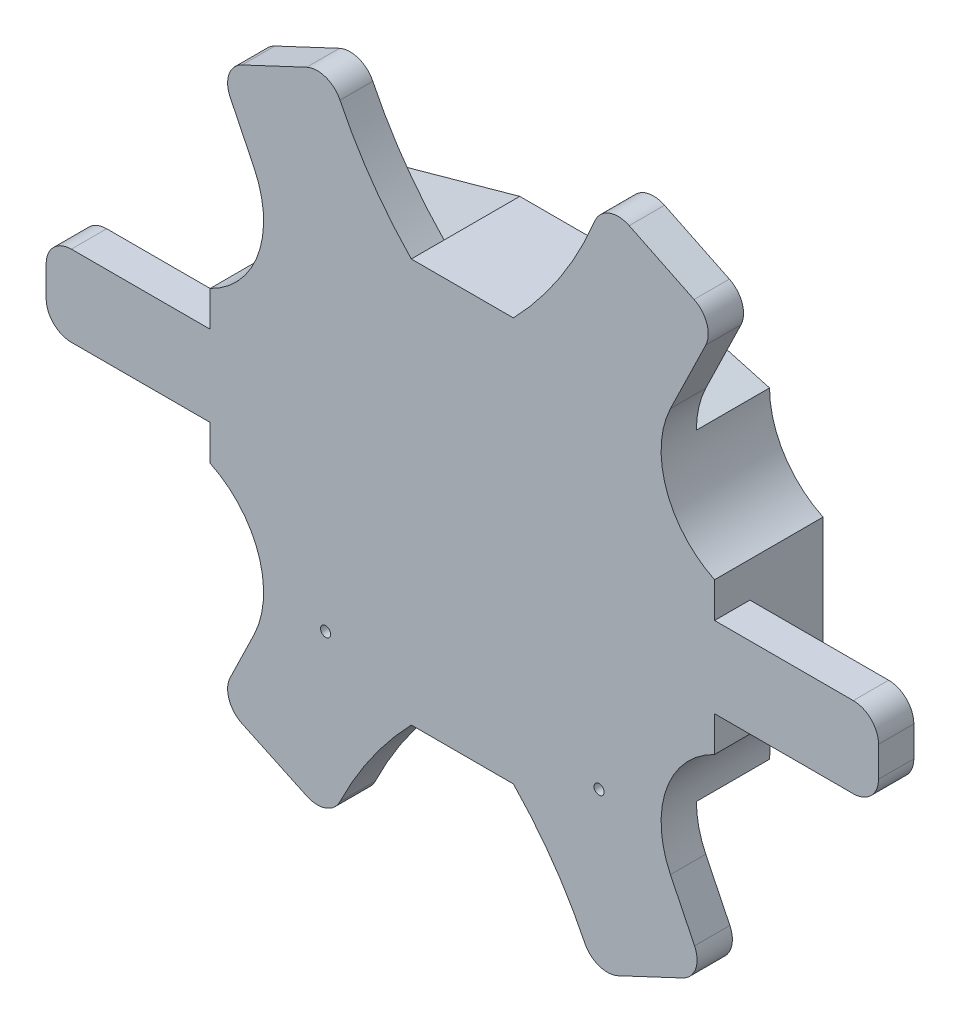
SolidWorks part; units mm, degrees
ref_plane "前视基准面" through (0, 0, 0) normal (0, 0, 1) x (1, 0, 0)
ref_plane "上视基准面" through (0, 0, 0) normal (0, 1, 0) x (1, 0, 0)
ref_plane "右视基准面" through (0, 0, 0) normal (1, 0, 0) x (0, 0, -1)
sketch "草图1" plane through (0, 0, 0) normal (0, 0, 1) x (1, 0, 0)
  line L0 (-50, -40) -> (-32.5, -40)
  line L1 (-50, 40) -> (50, 40)
  line L2 (-50, 40) -> (-50, -40)
  line L3 (-50, -40) -> (50, -40)
  line L4 (50, 40) -> (50, -40)
  line L5 (-50, 40) -> (50, -40) construction
  line L6 (-50, -40) -> (50, 40) construction
  line L7 (-32.5, -40) -> (32.5, -40)
  line L8 (-32.5, -40) -> (-32.5, 40)
  line L9 (-32.5, 40) -> (32.5, 40)
  line L10 (32.5, -40) -> (32.5, 40)
  line L11 (-32.5, -40) -> (32.5, 40) construction
  line L12 (-32.5, 40) -> (32.5, -40) construction
  line L13 (-50, 15) -> (50, 15)
  line L14 (-50, 15) -> (-50, -15)
  line L15 (-50, -15) -> (50, -15)
  line L16 (50, 15) -> (50, -15)
  line L17 (-50, 15) -> (50, -15) construction
  line L18 (-50, -15) -> (50, 15) construction
  line L19 (0, 0) -> (0, -24.7451) construction
  line L20 (0, -24.7451) -> (0, 0) construction
  line L21 (0, 0) -> (19.4056, 0) construction
  arc A0 (-50, -15) -> (-41.25, -40) centre (-58.125, -31.875) cw
  arc A1 (50, -15) -> (41.25, -40) centre (58.125, -31.875) ccw
  arc A2 (50, 15) -> (41.25, 40) centre (58.125, 31.875) cw
  arc A3 (-50, 15) -> (-41.25, 40) centre (-58.125, 31.875) ccw
  point P0 (0, 0)
  point P6 (0, 0)
  point P11 (0, 0)
  dimension "D1" = 100
  dimension "D2" = 80
  dimension "D3" = 65
  dimension "D4" = 30
  dimension "D5" = 0
extrude "凸台-拉伸1" add sketch "草图1" along normal blind 21.5 contours L8 L13 L10 L1 | A3 L13 L8 L1 | L13 A2 L1 L10 | L10 L15 L4 L13 | L8 L15 L10 L13 | L2 L15 L8 L13 | L15 A0 L3 L8 | L15 L8 L3 L10 | A1 L15 L10 L3
sketch "草图2" plane through (0, 0, 21.5) normal (0, 0, 1) x (1, 0, 0)
  line L0 (-41.25, 40) -> (41.25, 40) construction
  line L5 (41.25, 40) -> (0, 40) construction
  line L6 (-41.25, 40) -> (-56.5468, 71.4803)
  line L11 (0, 0) -> (0, 40) construction
  line L12 (10.1194, 40) -> (41.25, 40)
  line L13 (-87.5, 15) -> (-12.5, 15)
  line L14 (-41.25, 40) -> (-56.5468, 71.4803)
  line L16 (-56.5468, 71.4803) -> (-31.3626, 83.7177)
  line L19 (-87.5, 15) -> (-87.5, -15)
  line L20 (-10.1194, 40) -> (-41.25, 40)
  line L21 (56.5468, 71.4803) -> (31.3626, 83.7177)
  line L22 (41.25, 40) -> (56.5468, 71.4803)
  line L23 (-50, 15) -> (-50, -15) construction
  line L24 (-50, -15) -> (-50, 0) construction
  line L25 (-50, 0) -> (50, 0) construction
  line L26 (50, 15) -> (50, -15) construction
  line L27 (-10.1194, -40) -> (-41.25, -40)
  line L28 (-41.25, -40) -> (-56.5468, -71.4803)
  line L29 (-56.5468, -71.4803) -> (-31.3626, -83.7177)
  line L30 (56.5468, -71.4803) -> (31.3626, -83.7177)
  line L31 (41.25, -40) -> (56.5468, -71.4803)
  line L32 (10.1194, -40) -> (41.25, -40)
  line L33 (-87.5, -15) -> (-12.5, -15)
  line L34 (-12.5, 15) -> (-12.5, -15)
  line L35 (-87.5, 15) -> (-12.5, -15) construction
  line L36 (-87.5, -15) -> (-12.5, 15) construction
  line L37 (87.5, -15) -> (12.5, -15)
  line L38 (12.5, 15) -> (12.5, -15)
  line L39 (87.5, 15) -> (12.5, 15)
  line L40 (87.5, 15) -> (87.5, -15)
  arc A0 (-31.3626, 83.7177) -> (-10.1194, 40) centre (45.9871, 94.2833) ccw
  arc A1 (31.3626, 83.7177) -> (10.1194, 40) centre (-45.9871, 94.2833) cw
  arc A2 (-31.3626, -83.7177) -> (-10.1194, -40) centre (45.9871, -94.2833) cw
  arc A3 (31.3626, -83.7177) -> (10.1194, -40) centre (-45.9871, -94.2833) ccw
  line M6 (41.25, 40) -> (-41.25, 40)
  line M8 (-50, 15) -> (-50, -15)
  line M10 (-41.25, -40) -> (41.25, -40)
  line M12 (50, -15) -> (50, 15)
  dimension "D1" = 35
  dimension "D2" = 28
  dimension "D3" = 75
extrude "凸台-拉伸2" add sketch "草图2" against normal blind 7 contours L40 L39 L37 M12 | L21 A1 L22 M6 | A0 L16 L6 M6 | L19 L33 L13 M8 | L29 A2 L28 M10 | A3 L30 L31 M10
sketch "草图6" plane through (0, 0, 0) normal (0, 0, -1) x (-1, 0, 0)
  line L0 (10.1194, 40) -> (39.3958, 31.875)
  line L1 (39.3958, 31.875) -> (56.8372, 38.3489)
  line L2 (56.8372, 38.3489) -> (0, 62.6398)
  line L3 (0, 62.6398) -> (10.1194, 40)
  line L4 (-10.1194, 40) -> (-39.3958, 31.875)
  line L5 (41.25, 40) -> (-41.25, 40) construction
  line L6 (-41.25, 40) -> (-10.1194, 40) construction
  line L7 (-39.3958, 31.875) -> (-63.924, 42.3578)
  line L8 (-63.924, 42.3578) -> (-39.3958, 57.1479)
  line L9 (-39.3958, 57.1479) -> (-10.1194, 40)
  line L10 (-41.25, -40) -> (-10.1194, -40)
  line L11 (-10.1194, -40) -> (-39.3958, -31.875)
  line L12 (-39.3958, -31.875) -> (-55.112, -31.875)
  line L13 (-55.112, -31.875) -> (-41.25, -40)
  line L14 (41.25, -40) -> (10.1194, -40)
  line L15 (10.1194, -40) -> (39.3958, -31.875)
  line L16 (39.3958, -31.875) -> (58.125, -33.6788)
  line L17 (58.125, -33.6788) -> (41.25, -40)
  arc A0 (41.25, 40) -> (50, 15) centre (58.125, 31.875) ccw construction
  arc A1 (-50, 15) -> (-41.25, 40) centre (-58.125, 31.875) ccw construction
  arc A2 (-41.25, -40) -> (-50, -15) centre (-58.125, -31.875) ccw construction
  arc A3 (50, -15) -> (41.25, -40) centre (58.125, -31.875) ccw construction
extrude "切除-拉伸21" cut sketch "草图6" against normal blind 15 contours L3 L0 L1 L2
sketch "草图7" plane through (0, 0, 0) normal (0, 0, -1) x (-1, 0, 0)
  line L0 (-10.1194, -40) -> (-39.3958, -31.875)
  line L1 (-39.3958, -31.875) -> (-53.3584, -39.7712)
  line L2 (-53.3584, -39.7712) -> (-19.0866, -55.9873)
  line L3 (-19.0866, -55.9873) -> (-10.1194, -40)
  arc A0 (-41.25, -40) -> (-50, -15) centre (-58.125, -31.875) ccw construction
extrude "切除-拉伸23" cut sketch "草图7" against normal blind 14.5
sketch "草图9" plane through (0, 0, 0) normal (0, 0, -1) x (-1, 0, 0)
  line L0 (-10.1194, 40) -> (-39.3958, 31.875)
  line L1 (-39.3958, 31.875) -> (-58.125, 43.8836)
  line L2 (-58.125, 43.8836) -> (-7.923, 48.831)
  line L3 (-7.923, 48.831) -> (-10.1194, 40)
  arc A0 (-50, 15) -> (-41.25, 40) centre (-58.125, 31.875) ccw construction
  arc A1 (-50, 15) -> (-41.25, 40) centre (-58.125, 31.875) ccw construction
extrude "切除-拉伸24" cut sketch "草图9" against normal blind 14.5
sketch "草图10" plane through (0, 0, 0) normal (0, 0, -1) x (-1, 0, 0)
  line L0 (10.1194, 40) -> (42.2669, 21.9099)
  line L1 (42.2669, 21.9099) -> (59.8046, 30.9549)
  line L2 (59.8046, 30.9549) -> (0, 68.2027)
  line L3 (0, 68.2027) -> (10.1194, 40)
  arc A0 (39.3958, 31.875) -> (50, 15) centre (58.125, 31.875) ccw construction
extrude "切除-拉伸25" cut sketch "草图10" against normal blind 14.5
sketch "草图11" plane through (0, 0, 0) normal (0, 0, -1) x (-1, 0, 0)
  line L0 (10.1194, -40) -> (39.3958, -31.875)
  line L1 (39.3958, -31.875) -> (61.5861, -40)
  line L2 (61.5861, -40) -> (5.3442, -59.2957)
  line L3 (5.3442, -59.2957) -> (10.1194, -40)
  arc A0 (50, -15) -> (41.25, -40) centre (58.125, -31.875) ccw construction
extrude "切除-拉伸27" cut sketch "草图11" against normal blind 14.5 contours L3 L0 L1 L2
sketch "草图12" plane through (0, 0, 14.5) normal (0, 0, -1) x (-1, 0, 0)
  line L0 (10.1194, 40) -> (42.2669, 21.9099)
  line L1 (42.2669, 21.9099) -> (51.0834, 30.9549)
  line L2 (51.0834, 30.9549) -> (39.3958, 31.875)
  line L3 (39.3958, 31.875) -> (10.1194, 40) construction
  line L4 (39.3958, 31.875) -> (10.1194, 40)
  arc A0 (39.3958, 31.875) -> (42.2669, 21.9099) centre (58.125, 31.875) ccw construction
extrude "切除-拉伸28" cut sketch "草图12" against normal blind 0.5
sketch "草图13" plane through (0, 0, 14.5) normal (0, 0, -1) x (-1, 0, 0)
  line L0 (56.5468, -71.4803) -> (52.1763, -62.4859)
  line L1 (41.25, -40) -> (56.5468, -71.4803) construction
  line L3 (6.5457, -78.4133) -> (26.2576, -99.2847)
  line L4 (26.2576, -99.2847) -> (85.3933, -94.9365)
  line L5 (85.3933, -94.9365) -> (79.8856, -70.4496)
  line L6 (79.8856, -70.4496) -> (52.1763, -62.4859)
  line L7 (-56.5468, -71.4803) -> (-52.1763, -62.4859)
  line L8 (-41.25, -40) -> (-56.5468, -71.4803) construction
  line L10 (-3.3103, -66.9831) -> (-32.1225, -112.3189)
  line L11 (-32.1225, -112.3189) -> (-60.0284, -104.2987)
  line L12 (-60.0284, -104.2987) -> (-105.3484, -70.4496)
  line L13 (-105.3484, -70.4496) -> (-52.1763, -62.4859)
  line L14 (-52.1763, -62.4859) -> (-12.6565, -81.6893)
  line L15 (0, 0) -> (-120.4222, 0)
  line L16 (-120.4222, 0) -> (133.5136, 0)
  line L17 (-32.1225, 112.3189) -> (-60.0284, 104.2987)
  line L18 (-52.1763, 62.4859) -> (-12.6565, 81.6893)
  line L19 (-105.3484, 70.4496) -> (-52.1763, 62.4859)
  line L20 (-60.0284, 104.2987) -> (-105.3484, 70.4496)
  line L21 (79.8856, 70.4496) -> (52.1763, 62.4859)
  line L22 (85.3933, 94.9365) -> (79.8856, 70.4496)
  line L23 (26.2576, 99.2847) -> (85.3933, 94.9365)
  line L24 (6.5457, 78.4133) -> (26.2576, 99.2847)
  line L25 (52.1763, 62.4859) -> (6.5457, 78.4133)
  line L26 (-14.6432, 80.7239) -> (-32.1225, 112.3189)
  line L27 (52.1763, -62.4859) -> (56.5468, -71.4803)
  line L28 (52.1763, -62.4859) -> (8.4478, -83.7344)
  line L29 (56.5468, -71.4803) -> (12.8183, -92.7288)
  line L30 (8.4478, -83.7344) -> (12.8183, -92.7288)
  line L31 (-56.5468, -71.4803) -> (-52.1763, -62.4859)
  line L32 (-56.5468, -71.4803) -> (0.3344, -99.1199)
  line L33 (-52.1763, -62.4859) -> (4.705, -90.1256)
  line L34 (0.3344, -99.1199) -> (4.705, -90.1256)
  line L35 (52.1763, 62.4859) -> (56.5468, 71.4803)
  line L36 (52.1763, 62.4859) -> (-9.5134, 92.4621)
  line L37 (56.5468, 71.4803) -> (-5.1428, 101.4564)
  line L38 (-9.5134, 92.4621) -> (-5.1428, 101.4564)
  line L39 (-52.1763, 62.4859) -> (-56.5468, 71.4803)
  line L40 (-52.1763, 62.4859) -> (-11.0572, 82.4664)
  line L41 (-56.5468, 71.4803) -> (-15.4278, 91.4608)
  line L42 (-11.0572, 82.4664) -> (-15.4278, 91.4608)
  arc M12 (10.1194, -40) -> (31.3626, -83.7177) centre (-45.9871, -94.2833) cw
  line M13 (31.3626, -83.7177) -> (56.5468, -71.4803)
  line M14 (56.5468, -71.4803) -> (41.25, -40)
  dimension "D1" = 10
extrude "切除-拉伸32" cut sketch "草图13" against normal blind 10 contours L35 L37 L24 L36 | L41 L39 L18 L26 | L7 L32 L10 L14 | L28 M14 M12 M13
sketch "草图14" plane through (0, 0, 14.5) normal (0, 0, -1) x (-1, 0, 0)
  line L0 (50, 15) -> (50, -15) construction
  line L1 (87.5, -15) -> (50, -15)
  line L2 (87.5, -15) -> (87.5, -8)
  line L3 (87.5, -8) -> (50, -8)
  line L4 (50, -15) -> (50, -8)
  line L6 (87.5, 15) -> (50, 15)
  line L7 (87.5, 15) -> (87.5, 8)
  line L8 (87.5, 8) -> (50, 8)
  line L9 (50, 15) -> (50, 8)
  line L10 (0, 0) -> (0, 76.7434)
  line L11 (-87.5, 8) -> (-50, 8)
  line L12 (-50, 15) -> (-50, 8)
  line L13 (-87.5, 15) -> (-50, 15)
  line L14 (-87.5, 15) -> (-87.5, 8)
  line L15 (-87.5, -8) -> (-50, -8)
  line L16 (-50, -15) -> (-50, -8)
  line L17 (-87.5, -15) -> (-50, -15)
  line L18 (-87.5, -15) -> (-87.5, -8)
  line M9 (87.5, -15) -> (87.5, 15)
  line M11 (50, 15) -> (50, -15)
  line M12 (50, -15) -> (87.5, -15)
  dimension "D1" = 7
  dimension "D2" = 7
extrude "切除-拉伸33" cut sketch "草图14" against normal blind 10 contours L3 M9 M11 M12 | L18 L17 L16 L15 | L8 L9 L6 L7 | L11 L12 L13 L14
sketch "草图15" plane through (0, 0, 0) normal (0, 0, -1) x (-1, 0, 0)
  line L0 (39.3958, -31.875) -> (27.8329, -35.084)
  line L1 (0, 0) -> (0, -31.875) construction
  line L2 (10.1194, -40) -> (39.3958, -31.875) construction
  line L3 (27.8329, -35.084) -> (27.0975, -32.4342)
  line L4 (0, -31.875) -> (0, 0) construction
  line L5 (-18.8584, 0) -> (18.8584, 0) construction
  circle A2 centre (27.0975, -32.4342) radius 1
  circle A3 centre (-27.0975, -32.4342) radius 1
  dimension "D2" = 2.75
  dimension "D3" = 2
  dimension "D1" = 12
  dimension "D4" = 2.75
extrude "切除-拉伸34" cut sketch "草图15" against normal blind 30 contours A3 | A2
sketch "草图17" plane through (0, 0, 0) normal (0, 0, -1) x (-1, 0, 0)
  line L0 (-39.3958, 31.875) -> (-10.1194, 40)
  line L1 (-10.1194, 40) -> (10.1194, 40)
  line L2 (10.1194, 40) -> (0, 40)
  line L3 (0, 40) -> (0, 22.0171)
  line L4 (39.3958, 31.875) -> (10.1194, 40)
  line L5 (10.1194, 40) -> (42.2669, 21.9099)
  arc A0 (42.2669, 21.9099) -> (39.3958, 31.875) centre (58.125, 31.875) cw
  line M7 (42.2669, 21.9099) -> (10.1194, 40)
extrude "凸台-拉伸3" add sketch "草图17" against normal blind 20 contours A0 L4 M7
sketch "草图18" plane through (0, 0, 0) normal (0, 0, -1) x (-1, 0, 0)
  line L0 (0, 0) -> (14.8691, 0)
  circle A0 centre (-27.0975, -32.4342) radius 1
  circle A1 centre (27.0975, -32.4342) radius 1
  circle A2 centre (27.0975, 32.4342) radius 1
  circle A3 centre (-27.0975, 32.4342) radius 1
extrude "切除-拉伸35" cut sketch "草图18" against normal blind 20 contours A3 | A2
sketch "草图19" plane through (0, 0, 0) normal (0, 0, -1) x (-1, 0, 0)
  line L0 (-50, 15) -> (-50, -15)
  line L1 (-50, -15) -> (-50, 0)
  line L2 (-50, 0) -> (-47.25, 0)
  line L3 (50, 15) -> (50, -15)
  line L4 (50, -15) -> (50, 0)
  line L5 (50, 0) -> (47.25, 0)
  circle A0 centre (-47.25, 0) radius 1
  circle A1 centre (47.25, 0) radius 1
  dimension "D2" = 2
  dimension "D4" = 2
  dimension "D1" = 2.75
  dimension "D3" = 2.75
extrude "切除-拉伸36" cut sketch "草图19" against normal blind 20
sketch "草图20" plane through (0, 0, 0) normal (0, 0, -1) x (-1, 0, 0)
  line L1 (-27.5, 17.5) -> (27.5, 17.5)
  line L2 (-27.5, 17.5) -> (-27.5, -17.5)
  line L3 (-27.5, -17.5) -> (27.5, -17.5)
  line L4 (27.5, 17.5) -> (27.5, -17.5)
  line L5 (-27.5, 17.5) -> (27.5, -17.5) construction
  line L6 (-27.5, -17.5) -> (27.5, 17.5) construction
  point P0 (0, 0)
  dimension "D1" = 35
  dimension "D2" = 55
extrude "切除-拉伸37" cut sketch "草图20" against normal blind 20
sketch "草图21" plane through (-22.6362, 52.9656, 0) normal (0.393, -0.9195, 0) x (0.9195, 0.393, 0)
  line L1 (-22.4348, 15) -> (12.766, 15)
  line L2 (-22.4348, 15) -> (-22.4348, 4.0261)
  line L3 (-22.4348, 4.0261) -> (12.766, 4.0261)
  line L4 (12.766, 15) -> (12.766, 4.0261)
extrude "切除-拉伸38" cut sketch "草图21" against normal blind 26
ref_plane "基准面1" through (-51.2874, 62.9178, 14.5) normal (0.393, -0.9195, 0) x (-0.9195, -0.393, 0)
sketch "草图25" plane through (-34.5297, 71.0607, 0) normal (-0.4371, 0.8994, 0) x (0.8994, 0.4371, 0)
  line L1 (-18.6313, -15) -> (-22.9652, -15)
  line L2 (-18.6313, -15) -> (-18.6313, -11.4117)
  line L3 (-18.6313, -11.4117) -> (-22.9652, -11.4117)
  line L4 (-22.9652, -15) -> (-22.9652, -11.4117)
extrude "切除-拉伸41" cut sketch "草图25" against normal blind 26
sketch "草图26" plane through (17.6466, -8.5748, 0) normal (0.8994, -0.4371, 0) x (0, 0, -1)
  line L0 (-21.5, 79.0059) -> (-14.5, 79.0059)
sketch "草图28" plane through (0, 0, 14.5) normal (0, 0, -1) x (-1, 0, 0)
  line L0 (-52.1763, 62.4859) -> (-50.4281, 58.8882)
  line L1 (-52.1763, 62.4859) -> (-16.9488, 79.6036)
  line L2 (-50.4281, 58.8882) -> (-15.2006, 76.0058)
  line L3 (-16.9488, 79.6036) -> (-15.2006, 76.0058)
  line L4 (-41.25, 40) -> (-52.1763, 62.4859) construction
  line L5 (0, 0) -> (0, 49.7835)
  line L6 (0, 49.7835) -> (0, 0)
  line L7 (0, -1.8015) -> (-48.6857, -1.8015)
  line L8 (-48.6857, -1.8015) -> (48.6857, -1.8015)
  line L9 (50.4281, 58.8882) -> (15.2006, 76.0058)
  line L10 (16.9488, 79.6036) -> (15.2006, 76.0058)
  line L11 (52.1763, 62.4859) -> (16.9488, 79.6036)
  line L12 (52.1763, 62.4859) -> (50.4281, 58.8882)
  line L13 (52.1763, -66.089) -> (50.4281, -62.4912)
  line L14 (52.1763, -66.089) -> (16.9488, -83.2067)
  line L15 (16.9488, -83.2067) -> (15.2006, -79.6089)
  line L16 (50.4281, -62.4912) -> (15.2006, -79.6089)
  line L17 (-50.4281, -62.4912) -> (-15.2006, -79.6089)
  line L18 (-16.9488, -83.2067) -> (-15.2006, -79.6089)
  line L19 (-52.1763, -66.089) -> (-16.9488, -83.2067)
  line L20 (-52.1763, -66.089) -> (-50.4281, -62.4912)
  line L21 (-50.4281, -62.4912) -> (-52.1763, -66.089)
  line L22 (-50.4281, -62.4912) -> (-58.7905, -58.4278)
  line L23 (-52.1763, -66.089) -> (-60.5387, -62.0255)
  line L24 (-58.7905, -58.4278) -> (-60.5387, -62.0255)
  line L25 (50.4281, -62.4912) -> (52.1763, -66.089)
  line L26 (50.4281, -62.4912) -> (56.3121, -59.6321)
  line L27 (52.1763, -66.089) -> (58.0603, -63.2298)
  line L28 (56.3121, -59.6321) -> (58.0603, -63.2298)
  dimension "D1" = 4
extrude "切除-拉伸42" cut sketch "草图28" against normal blind 23 contours L13 L16 L15 L14 | L28 L26 L13 L27 | L20 L19 L18 L17 | L22 L24 L23 L20 | L3 L1 L0 L2 | L12 L11 L10 L9
sketch "草图29" plane through (0, 0, 14.5) normal (0, 0, -1) x (-1, 0, 0)
  line L0 (-87.5, 8) -> (-87.5, -8)
  line L1 (-87.5, 8) -> (-82.5, 8)
  line L2 (-87.5, -8) -> (-82.5, -8)
  line L3 (-82.5, 8) -> (-82.5, -8)
  line L4 (87.5, 8) -> (87.5, -8)
  line L5 (87.5, 8) -> (82.5, 8)
  line L6 (87.5, -8) -> (82.5, -8)
  line L7 (82.5, 8) -> (82.5, -8)
  dimension "D1" = 5
  dimension "D2" = 5
extrude "切除-拉伸43" cut sketch "草图29" against normal blind 23
sketch "草图30" plane through (0, 0, 0) normal (0, 0, -1) x (-1, 0, 0)
  line L0 (-27.5, 0) -> (-37.5, 0) construction
  line L1 (-27.5, 17.5) -> (-27.5, -17.5) construction
  line L2 (27.5, 0) -> (37.5, 0) construction
  line L3 (27.5, -17.5) -> (27.5, 17.5) construction
  circle A0 centre (-37.5, 0) radius 1.55
  circle A1 centre (37.5, 0) radius 1.55
  dimension "D2" = 3.1
  dimension "D4" = 3.1
  dimension "D1" = 10
  dimension "D3" = 10
extrude "切除-拉伸44" cut sketch "草图30" against normal blind 10 contours A0 | A1
sketch "草图31" plane through (0, 0, 0) normal (0, 0, -1) x (-1, 0, 0)
  line L0 (37.5, 0) -> (-35.5, 0)
  circle A0 centre (-35.5, 0) radius 1.55
  dimension "D2" = 3.1
  dimension "D1" = 73
extrude "切除-拉伸45" cut sketch "草图31" against normal blind 6.1008
sketch "草图32" plane through (0, 0, 0) normal (0, 0, -1) x (-1, 0, 0)
  circle A0 centre (-37.5, 0) radius 1.55
extrude "凸台-拉伸4" add sketch "草图32" against normal blind 15
sketch "草图33" plane through (0, 0, 0) normal (0, 0, -1) x (-1, 0, 0)
  circle A0 centre (-35.5, 0) radius 1.55
extrude "切除-拉伸46" cut sketch "草图33" against normal blind 12
sketch "草图34" plane through (0, 0, 14.5) normal (0, 0, -1) x (-1, 0, 0)
  line L0 (-50, -8) -> (-77.5, -8)
  line L1 (-82.5, -3) -> (-82.5, 3)
  line L2 (-77.5, 8) -> (-50, 8)
  line L3 (-50, 15) -> (-50, -15) construction
  line L4 (-82.5, 8) -> (-50, 8) construction
  line L5 (-77.5, 8) -> (-82.5, 8)
  line L6 (-82.5, 8) -> (-82.5, 3)
  line L7 (-82.5, -8) -> (-77.5, -8)
  line L8 (-82.5, -3) -> (-82.5, -8)
  arc A0 (-82.5, -3) -> (-77.5, -8) centre (-77.5, -3) ccw
  arc A1 (-77.5, 8) -> (-82.5, 3) centre (-77.5, 3) ccw
  point P13 (-82.5, -8)
  point P16 (-82.5, 8)
  line M6 (-50, 8) -> (-82.5, 8)
  line M7 (-82.5, 8) -> (-82.5, -8)
  line M8 (-82.5, -8) -> (-50, -8)
  dimension "D1" = 5
extrude "切除-拉伸49" cut sketch "草图34" against normal blind 10 contours A0 M7 M8 | A1 M6 M7
sketch "草图35" plane through (0, 0, 14.5) normal (0, 0, -1) x (-1, 0, 0)
  line L0 (50.0163, 8) -> (77.5, 8)
  line L1 (82.5, 8) -> (50, 8) construction
  line L2 (82.5, 8) -> (82.5, -8) construction
  line L3 (82.5, 3) -> (82.5, -3)
  line L4 (77.5, -8) -> (50, -8)
  line L5 (82.5, -8) -> (50, -8) construction
  line L6 (77.5, 8) -> (82.5, 8)
  line L7 (82.5, 8) -> (82.5, -8.4667)
  line L8 (82.5, -8.4667) -> (77.5, -8)
  arc A0 (82.5, 3) -> (77.5, 8) centre (77.5, 3) ccw
  arc A1 (82.5, -3) -> (77.5, -8) centre (77.5, -3) cw
  point P12 (82.5, 8)
  point P15 (82.5, -8)
  line M1 (50, -8) -> (82.5, -8)
  line M2 (82.5, -8) -> (82.5, 8)
  line M3 (82.5, 8) -> (50, 8)
  dimension "D1" = 5
extrude "切除-拉伸50" cut sketch "草图35" against normal blind 25 contours A0 M2 M3 | A1 M2 M1
sketch "草图36" plane through (0, 0, 14.5) normal (0, 0, -1) x (-1, 0, 0)
  line L0 (-45.9309, 61.0734) -> (-33.0777, 67.319)
  line L1 (-48.2428, 54.391) -> (-41.25, 40)
  line L2 (-27.5, 0) -> (27.5, 0)
  line L3 (-27.5, 17.5) -> (-27.5, -17.5) construction
  line L4 (27.5, -17.5) -> (27.5, 17.5) construction
  line L5 (27.5, 0) -> (0, 0)
  line L6 (0, 0) -> (0, 40)
  line L7 (10.1194, 40) -> (-10.1194, 40) construction
  line L8 (-45.9309, -61.0734) -> (-33.0777, -67.319)
  line L9 (33.0777, -67.319) -> (45.9309, -61.0734)
  line L10 (26.265, -64.7156) -> (16.255, -74.7256)
  line L11 (16.255, -74.7256) -> (33.0777, -82.9)
  line L12 (33.0777, -82.9) -> (53.4138, -73.0184)
  line L13 (53.4138, -73.0184) -> (58.1214, -59.4115)
  line L14 (58.1214, -59.4115) -> (48.2428, -54.391)
  line L15 (-26.265, -64.7156) -> (-14.7187, -84.3905)
  line L16 (-14.7187, -84.3905) -> (-54.0273, -84.3905)
  line L17 (-54.0273, -84.3905) -> (-58.9039, -66.2149)
  line L18 (-58.9039, -66.2149) -> (-58.9039, -48.4808)
  line L19 (-58.9039, -48.4808) -> (-48.2428, -54.391)
  line L20 (-26.265, 64.7156) -> (-25.3062, 81.0959)
  line L21 (-25.3062, 81.0959) -> (-42.8998, 80.2776)
  line L22 (-42.8998, 80.2776) -> (-39.5043, 72.9057)
  line L23 (-39.5043, 72.9057) -> (-33.0777, 67.319)
  line L24 (-45.9309, 61.0734) -> (-63.9834, 67.319)
  line L25 (-63.9834, 67.319) -> (-64.7048, 65.234)
  line L26 (-64.7048, 65.234) -> (-70.7158, 54.391)
  line L27 (-70.7158, 54.391) -> (-54.9572, 54.391)
  line L28 (-54.9572, 54.391) -> (-48.2428, 54.391)
  line L29 (26.265, 64.7156) -> (17.7678, 67.6553)
  line L30 (17.7678, 67.6553) -> (26.8486, 84.0357)
  line L31 (26.8486, 84.0357) -> (28.8201, 82.9428)
  line L32 (28.8201, 82.9428) -> (36.6358, 76.1485)
  line L33 (36.6358, 76.1485) -> (33.0777, 67.319)
  line L34 (45.9309, 61.0734) -> (49.061, 72.9057)
  line L35 (49.061, 72.9057) -> (54.9946, 67.7476)
  line L36 (54.9946, 67.7476) -> (55.5142, 56.5762)
  line L37 (55.5142, 56.5762) -> (53.6802, 49.6434)
  line L38 (53.6802, 49.6434) -> (48.2428, 54.391)
  arc A0 (-26.265, 64.7156) -> (-10.1194, 40) centre (45.9871, 94.2833) ccw
  arc A1 (-33.0777, 67.319) -> (-26.265, 64.7156) centre (-30.8925, 62.8218) cw
  arc A2 (-48.2428, 54.391) -> (-45.9309, 61.0734) centre (-43.7457, 56.5762) cw
  arc A3 (48.2428, 54.391) -> (45.9309, 61.0734) centre (43.7457, 56.5762) ccw
  arc A4 (33.0777, 67.319) -> (26.265, 64.7156) centre (30.8925, 62.8218) ccw
  arc A5 (-48.2428, -54.391) -> (-45.9309, -61.0734) centre (-43.7457, -56.5762) ccw
  arc A6 (-33.0777, -67.319) -> (-26.265, -64.7156) centre (-30.8925, -62.8218) ccw
  arc A7 (33.0777, -67.319) -> (26.265, -64.7156) centre (30.8925, -62.8218) cw
  arc A8 (48.2428, -54.391) -> (45.9309, -61.0734) centre (43.7457, -56.5762) cw
  point P11 (-28.1188, 69.7287)
  point P14 (-50.4281, 58.8882)
  arc M2 (-10.1194, 40) -> (-28.1188, 69.7287) centre (45.9871, 94.2833) cw
  line M3 (-28.1188, 69.7287) -> (-50.4281, 58.8882)
  line M4 (-50.4281, 58.8882) -> (-41.25, 40)
  dimension "D1" = 5
  dimension "D2" = 5
extrude "切除-拉伸51" cut sketch "草图36" against normal blind 25 contours L22 L23 L20 L21 M3 M2 | A4 L33 L32 L31 L30 L29 | A3 L38 L37 L36 L35 L34 | L27 L28 L24 L25 L26 M4 M3 | A6 L8 A5 L19 L18 L17 L16 L15 | L14 A8 L9 A7 L10 L11 L12 L13
sketch "草图37" plane through (0, 0, 14.5) normal (0, 0, -1) x (-1, 0, 0)
  line L0 (-50.4281, 58.8882) -> (-49.4563, 56.8882)
  line L1 (-50.4281, 58.8882) -> (-22.5323, 72.4432)
  line L2 (-49.4563, 56.8882) -> (-21.5605, 70.4432)
  line L3 (-22.5323, 72.4432) -> (-21.5605, 70.4432)
  line L4 (-41.25, 40) -> (-50.4281, 58.8882) construction
  line L5 (0, 0) -> (20.5618, 0)
  line L6 (20.5618, 0) -> (0, 0)
  line L7 (0, 0) -> (0, 31.9309)
  line L8 (49.4563, 56.8882) -> (21.5605, 70.4432)
  line L9 (22.5323, 72.4432) -> (21.5605, 70.4432)
  line L10 (50.4281, 58.8882) -> (22.5323, 72.4432)
  line L11 (50.4281, 58.8882) -> (49.4563, 56.8882)
  line L12 (50.4281, -58.8882) -> (49.4563, -56.8882)
  line L13 (50.4281, -58.8882) -> (22.5323, -72.4432)
  line L14 (22.5323, -72.4432) -> (21.5605, -70.4432)
  line L15 (49.4563, -56.8882) -> (21.5605, -70.4432)
  line L16 (-49.4563, -56.8882) -> (-21.5605, -70.4432)
  line L17 (-22.5323, -72.4432) -> (-21.5605, -70.4432)
  line L18 (-50.4281, -58.8882) -> (-22.5323, -72.4432)
  line L19 (-50.4281, -58.8882) -> (-49.4563, -56.8882)
  arc M11 (-10.1194, 40) -> (-28.1188, 69.7287) centre (45.9871, 94.2833) cw
  dimension "D1" = 2
extrude "切除-拉伸52" cut sketch "草图37" against normal blind 25 contours L19 L18 L17 L16 | L12 L15 L14 L13 | L11 L10 L9 L8 | L3 L1 L2 M11
sketch "草图38" plane through (0, 0, 14.5) normal (0, 0, -1) x (-1, 0, 0)
  line L0 (-41.25, 40) -> (-48.2428, 54.391)
  line L1 (-45.9309, 61.0734) -> (-33.0777, 67.319)
  line L2 (-48.2428, 54.391) -> (-80.4737, 72.3605)
  line L3 (-80.4737, 72.3605) -> (-37.0273, 93.4719)
  line L4 (-37.0273, 93.4719) -> (-21.2855, 73.9284)
  line L5 (-21.2855, 73.9284) -> (-26.265, 64.7156)
  line L6 (0, 0) -> (-21.2855, 0)
  line L7 (-21.2855, 0) -> (0, 0)
  line L8 (0, 0) -> (0, -15.6861)
  arc A0 (-45.9309, 61.0734) -> (-48.2428, 54.391) centre (-43.7457, 56.5762) ccw
  arc A1 (-10.1194, 40) -> (-26.265, 64.7156) centre (45.9871, 94.2833) cw
  arc A2 (-33.0777, 67.319) -> (-26.265, 64.7156) centre (-30.8925, 62.8218) cw
  point P8 (-50.4281, 58.8882)
  point P14 (-28.1188, 69.7287)
  arc M6 (-10.1194, 40) -> (-28.1188, 69.7287) centre (45.9871, 94.2833) cw
  line M7 (-28.1188, 69.7287) -> (-50.4281, 58.8882)
  line M8 (-50.4281, 58.8882) -> (-41.25, 40)
  dimension "D1" = 5
  dimension "D2" = 5
extrude "切除-拉伸55" cut sketch "草图38" against normal blind 25 contours A2 M7 M6 | A0 M7 M8
sketch "草图39" plane through (0, 0, 15) normal (0, 0, -1) x (-1, 0, 0)
  line L0 (48.2428, 54.391) -> (26.265, 64.7156)
  line L1 (26.265, 64.7156) -> (26.265, 71.3681)
  line L2 (26.265, 71.3681) -> (43.7457, 64.7156)
  line L3 (43.7457, 64.7156) -> (54.4532, 55.7897)
  line L4 (54.4532, 55.7897) -> (48.2428, 54.391)
  arc A0 (28.3658, 67.1364) -> (26.265, 64.7156) centre (30.8925, 62.8218) ccw construction
  arc A1 (10.1194, 40) -> (26.265, 64.7156) centre (-45.9871, 94.2833) ccw construction
extrude "切除-拉伸56" cut sketch "草图39" against normal blind 25
sketch "草图40" plane through (0, 0, 15) normal (0, 0, -1) x (-1, 0, 0)
  line L0 (46.0278, 49.8326) -> (41.25, 40)
  line L1 (41.25, 40) -> (48.2428, 54.391)
  line L2 (30.8708, 62.5441) -> (43.655, 56.5442)
  line L3 (24.2481, 60.2007) -> (21.2149, 69.5097)
  line L4 (21.2149, 69.5097) -> (39.6913, 70.9899)
  line L5 (39.6913, 70.9899) -> (58.6843, 58.0178)
  line L6 (58.6843, 58.0178) -> (64.7781, 52.0179)
  line L7 (64.7781, 52.0179) -> (46.0278, 49.8326)
  arc A0 (24.2481, 60.2007) -> (10.1194, 40) centre (-45.9871, 94.2833) cw
  arc A1 (10.1194, 40) -> (26.265, 64.7156) centre (-45.9871, 94.2833) ccw construction
  arc A2 (43.655, 56.5442) -> (46.0278, 49.8326) centre (41.5307, 52.0179) cw
  arc A3 (24.2481, 60.2007) -> (30.8708, 62.5441) centre (28.7465, 58.0178) cw
  point P16 (26.2616, 64.7073)
  line M2 (41.25, 40) -> (48.2428, 54.391)
  line M3 (48.2428, 54.391) -> (26.265, 64.7156)
  arc M4 (26.265, 64.7156) -> (10.1194, 40) centre (-45.9871, 94.2833) cw
  dimension "D1" = 5
  dimension "D2" = 5
extrude "切除-拉伸59" cut sketch "草图40" against normal blind 25 contours A3 L2 A2 M4 M2 M3
sketch "草图41" plane through (0, 0, 14.5) normal (0, 0, -1) x (-1, 0, 0)
  line L0 (-48.2428, -54.391) -> (-26.265, -64.7156)
  line L1 (-26.265, -64.7156) -> (-33.3072, -81.924)
  line L2 (-33.3072, -81.924) -> (-55.0773, -68.9395)
  line L3 (-55.0773, -68.9395) -> (-59.7694, -58.1933)
  line L4 (-59.7694, -58.1933) -> (-48.2428, -54.391)
extrude "切除-拉伸60" cut sketch "草图41" against normal blind 25
sketch "草图42" plane through (0, 0, 14.5) normal (0, 0, -1) x (-1, 0, 0)
  line L0 (-41.25, -40) -> (-46.0287, -49.8343)
  line L1 (-43.6574, -56.5451) -> (-30.8755, -62.5497)
  line L2 (-46.0287, -49.8343) -> (-48.2428, -54.391)
  line L3 (-48.2428, -54.391) -> (-26.265, -64.7156)
  line L4 (-26.265, -64.7156) -> (-24.251, -60.2066)
  arc A0 (-10.1194, -40) -> (-24.251, -60.2066) centre (45.9871, -94.2833) ccw
  arc A1 (-30.8755, -62.5497) -> (-24.251, -60.2066) centre (-28.7495, -58.0241) ccw
  arc A2 (-43.6574, -56.5451) -> (-46.0287, -49.8343) centre (-41.5315, -52.0195) cw
  point P11 (-26.265, -64.7156)
  point P14 (-48.2428, -54.391)
  line M6 (-41.25, -40) -> (-48.2428, -54.391)
  line M7 (-48.2428, -54.391) -> (-26.265, -64.7156)
  arc M8 (-26.265, -64.7156) -> (-10.1194, -40) centre (45.9871, -94.2833) cw
  dimension "D1" = 5
  dimension "D2" = 5
extrude "切除-拉伸61" cut sketch "草图42" against normal blind 25 contours A2 M7 M6 | A1 M7 M8
sketch "草图43" plane through (0, 0, 14.5) normal (0, 0, -1) x (-1, 0, 0)
  line L0 (48.2428, -54.391) -> (26.265, -64.7156)
  line L1 (26.265, -64.7156) -> (26.265, -68.8252)
  line L2 (26.265, -68.8252) -> (37.2539, -68.8252)
  line L3 (37.2539, -68.8252) -> (50.7557, -62.4825)
  line L4 (50.7557, -62.4825) -> (52.3934, -53.454)
  line L5 (52.3934, -53.454) -> (48.2428, -54.391)
extrude "切除-拉伸62" cut sketch "草图43" against normal blind 25
sketch "草图44" plane through (0, 0, 14.5) normal (0, 0, -1) x (-1, 0, 0)
  line L0 (41.25, -40) -> (46.0287, -49.8343)
  line L1 (43.6574, -56.5451) -> (30.8755, -62.5497)
  line L2 (24.251, -60.2066) -> (26.265, -64.7156)
  line L3 (26.265, -64.7156) -> (30.8755, -62.5497)
  line L4 (43.6574, -56.5451) -> (48.2428, -54.391)
  line L5 (48.2428, -54.391) -> (46.0287, -49.8343)
  arc A0 (24.251, -60.2066) -> (10.1194, -40) centre (-45.9871, -94.2833) ccw
  arc A1 (30.8755, -62.5497) -> (24.251, -60.2066) centre (28.7495, -58.0241) cw
  arc A2 (46.0287, -49.8343) -> (43.6574, -56.5451) centre (41.5315, -52.0195) cw
  point P11 (26.265, -64.7156)
  point P14 (48.2428, -54.391)
  arc M1 (10.1194, -40) -> (26.265, -64.7156) centre (-45.9871, -94.2833) cw
  line M2 (26.265, -64.7156) -> (48.2428, -54.391)
  line M3 (48.2428, -54.391) -> (41.25, -40)
  dimension "D1" = 5
  dimension "D2" = 5
extrude "切除-拉伸63" cut sketch "草图44" against normal blind 25 contours A1 M2 M1 | A2 M3 M2
